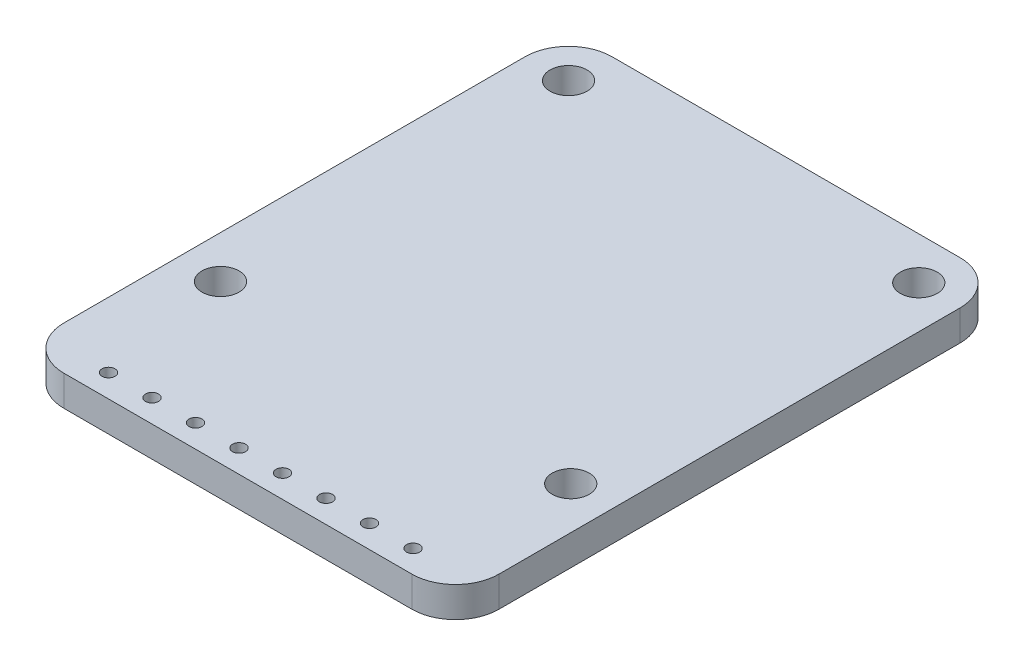
SolidWorks part; units mm, degrees
ref_plane "Front Plane" through (0, 0, 0) normal (0, 0, 1) x (1, 0, 0)
ref_plane "Top Plane" through (0, 0, 0) normal (0, 1, 0) x (1, 0, 0)
ref_plane "Right Plane" through (0, 0, 0) normal (1, 0, 0) x (0, 0, -1)
sketch "Sketch1" plane through (0, 0, 0) normal (0, 1, 0) x (1, 0, 0)
  line L1 (10.16, 16.002) -> (-10.16, 16.002)
  line L2 (12.7, 13.462) -> (12.7, -13.462)
  line L3 (10.16, -16.002) -> (-10.16, -16.002)
  line L4 (-12.7, 13.462) -> (-12.7, -13.462)
  line L5 (12.7, 16.002) -> (-12.7, -16.002) construction
  line L6 (12.7, -16.002) -> (-12.7, 16.002) construction
  line L14 (0, 0) -> (0, 10.4198) construction
  line L15 (-10.16, 13.462) -> (10.16, -13.462) construction
  line L16 (10.16, 13.462) -> (-10.16, -13.462) construction
  line L17 (0, 0) -> (-8.3012, 0) construction
  arc A0 (10.16, 16.002) -> (12.7, 13.462) centre (10.16, 13.462) cw
  arc A1 (12.7, -13.462) -> (10.16, -16.002) centre (10.16, -13.462) cw
  arc A2 (-10.16, -16.002) -> (-12.7, -13.462) centre (-10.16, -13.462) cw
  arc A3 (-10.16, 16.002) -> (-12.7, 13.462) centre (-10.16, 13.462) ccw
  circle A8 centre (-10.2235, 13.5255) radius 1.0795
  circle A9 centre (10.2235, 13.5255) radius 1.0795
  circle A10 centre (-10.2235, -6.7945) radius 1.0795
  circle A11 centre (10.2235, -6.7945) radius 1.0795
  point P0 (0, 0)
  dimension "D1" = 2.54
  dimension "D9" = 2.159
  dimension "D4" = 2.4765
  dimension "D6" = 18.161
  dimension "D2" = 32.004
  dimension "D3" = 25.4
  dimension "D5" = 1.397
extrude "Boss-Extrude1" add sketch "Sketch1" along normal blind 1.778
sketch "Sketch2" plane through (0, 0, 0) normal (0, -1, 0) x (1, 0, 0)
  line L0 (-10.16, 16.002) -> (10.16, 16.002) construction
  line L1 (-6.604, 16.002) -> (6.604, 16.002)
  line L2 (-6.604, 16.002) -> (-6.604, 13.335)
  line L3 (-6.604, 13.335) -> (6.604, 13.335)
  line L4 (6.604, 16.002) -> (6.604, 13.335)
  line L5 (0, 0) -> (0, 2.4773) construction
  dimension "D1" = 13.208
  dimension "D2" = 2.667
  dimension "D3" = 0
extrude "Boss-Extrude2" add sketch "Sketch2" along normal blind 2.159
sketch "Sketch3" plane through (0, -2.159, 0) normal (0, -1, 0) x (1, 0, 0)
  line L0 (-6.604, 14.6685) -> (6.604, 14.6685) construction
  line L1 (-6.604, 16.002) -> (-6.604, 13.335) construction
  line L2 (6.604, 13.335) -> (6.604, 16.002) construction
  line L3 (0, 0) -> (0, 11.811) construction
  circle A0 centre (-8.89, 14.6685) radius 0.381
  circle A1 centre (-6.35, 14.6685) radius 0.381
  circle A2 centre (-3.81, 14.6685) radius 0.381
  circle A3 centre (6.35, 14.6685) radius 0.381
  circle A4 centre (8.89, 14.6685) radius 0.381
  circle A5 centre (-1.27, 14.6685) radius 0.381
  circle A6 centre (1.27, 14.6685) radius 0.381
  circle A7 centre (3.81, 14.6685) radius 0.381
  dimension "D2" = 2.54
  dimension "D3" = 0.762
  dimension "D4" = 2.54
  dimension "D1" = 2.54
  dimension "D5" = 2.54
extrude "Cut-Extrude1" cut sketch "Sketch3" against normal through all
sketch "Sketch4" plane through (-12.7, 0, 0) normal (-1, 0, 0) x (0, 0, 1)
  line L0 (-13.462, 0) -> (13.462, 0) construction
  line L1 (3.3678, 0) -> (17.1347, 0)
  line L2 (3.3678, 0) -> (3.3678, -3.8704)
  line L3 (3.3678, -3.8704) -> (17.1347, -3.8704)
  line L4 (17.1347, 0) -> (17.1347, -3.8704)
extrude "Cut-Extrude2" cut sketch "Sketch4" against normal through all
sketch "Sketch5" plane through (0, 0, 0) normal (0, -1, 0) x (1, 0, 0)
  text T0 "Micro-SD"
extrude "Cut-Extrude3" cut sketch "Sketch5" against normal blind 0.0254
sketch "Sketch9" plane through (0, 0, 0) normal (0, -1, 0) x (1, 0, 0)
  line L0 (0, -16.002) -> (0, 8.5891) construction
  line L1 (-7.0485, -0.762) -> (7.0485, -0.762)
  line L2 (-7.0485, -0.762) -> (-7.0485, -16.002)
  line L3 (-7.0485, -16.002) -> (7.0485, -16.002)
  line L4 (7.0485, -0.762) -> (7.0485, -16.002)
  line L5 (10.16, -16.002) -> (-10.16, -16.002) construction
  dimension "D1" = 14.097
  dimension "D2" = 15.24
extrude "Boss-Extrude4" add sketch "Sketch9" along normal blind 1.524
